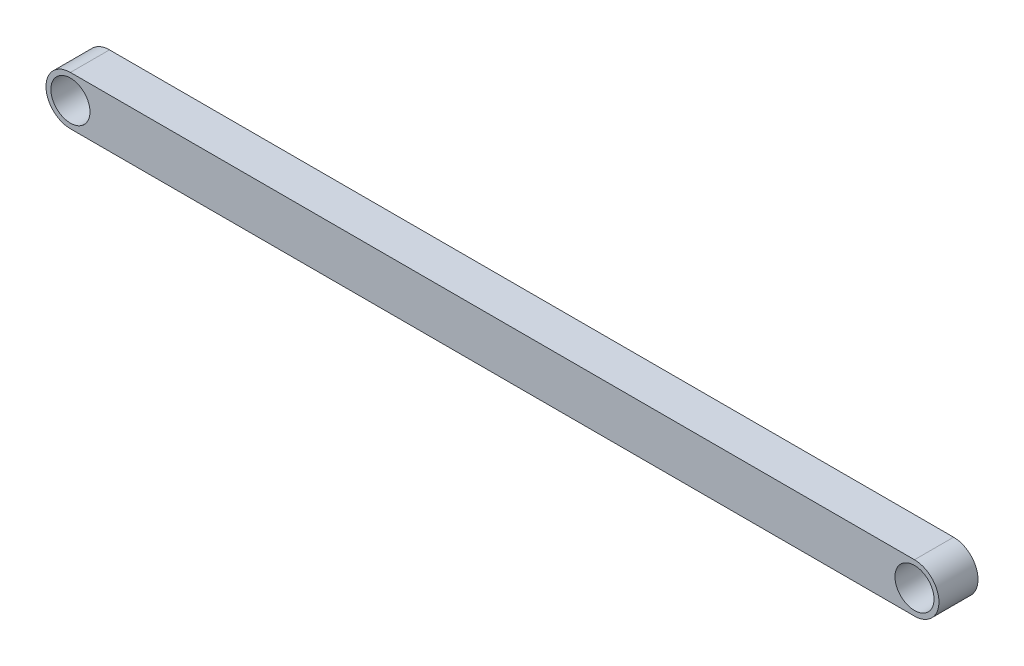
SolidWorks part; units mm, degrees
ref_plane "Front Plane" through (0, 0, 0) normal (0, 0, 1) x (1, 0, 0)
ref_plane "Top Plane" through (0, 0, 0) normal (0, 1, 0) x (1, 0, 0)
ref_plane "Right Plane" through (0, 0, 0) normal (1, 0, 0) x (0, 0, -1)
sketch "Sketch1" plane through (0, 0, 0) normal (0, 0, 1) x (1, 0, 0)
  line L0 (0, 0) -> (43.2, 0) construction
  line L1 (0, 1.25) -> (43.2, 1.25)
  line L2 (0, -1.25) -> (43.2, -1.25)
  arc A0 (0, 1.25) -> (0, -1.25) centre (0, 0) ccw
  arc A1 (43.2, -1.25) -> (43.2, 1.25) centre (43.2, 0) ccw
  circle A2 centre (0, 0) radius 1
  circle A3 centre (43.2, 0) radius 1
  point P3 (21.6, 0)
  point P12 (0, 0)
  point P13 (0, 0)
  dimension "D1" = 2
  dimension "D2" = 2
  dimension "D3" = 43.2
  dimension "D4" = 2.5
extrude "Boss-Extrude1" add sketch "Sketch1" along normal blind 2
